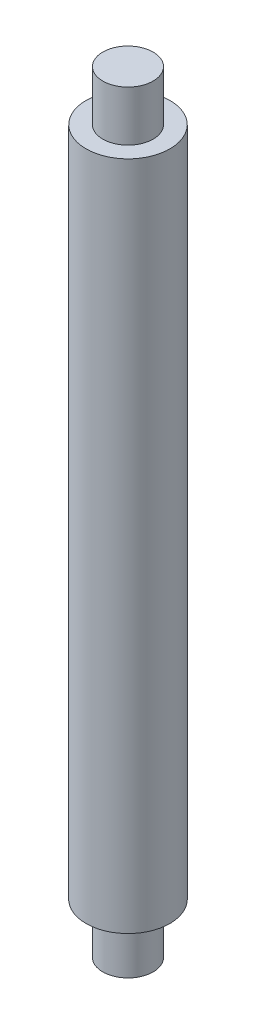
SolidWorks part; units mm, degrees
ref_plane "前视基准面" through (0, 0, 0) normal (0, 0, 1) x (1, 0, 0)
ref_plane "上视基准面" through (0, 0, 0) normal (0, 1, 0) x (1, 0, 0)
ref_plane "右视基准面" through (0, 0, 0) normal (1, 0, 0) x (0, 0, -1)
other "Configuration Table"
sketch "草图1" plane through (0, 0, 0) normal (0, 1, 0) x (1, 0, 0)
  circle A0 centre (0, 0) radius 2.5
  dimension "D1" = 5
extrude "凸台-拉伸2" add sketch "草图1" against normal mid plane 40
sketch "草图2" plane through (0, 20, 0) normal (0, 1, 0) x (1, 0, 0)
  circle A0 centre (0, 0) radius 1.5
  dimension "D1" = 3
extrude "凸台-拉伸3" add sketch "草图2" along normal blind 3
sketch "草图3" plane through (0, -20, 0) normal (0, -1, 0) x (1, 0, 0)
  circle A0 centre (0, 0) radius 1.5
  dimension "D1" = 3
extrude "凸台-拉伸4" add sketch "草图3" along normal blind 3
